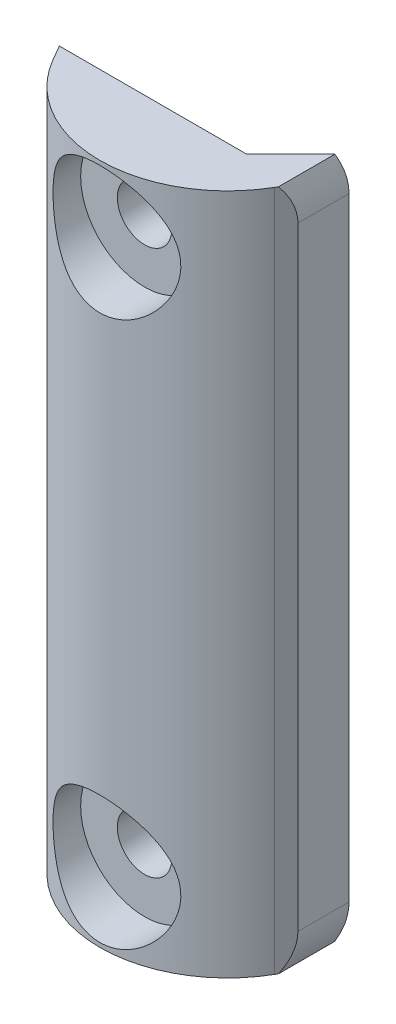
SolidWorks part; units mm, degrees
ref_plane "前视基准面" through (0, 0, 0) normal (0, 0, 1) x (1, 0, 0)
ref_plane "上视基准面" through (0, 0, 0) normal (0, 1, 0) x (1, 0, 0)
ref_plane "右视基准面" through (0, 0, 0) normal (1, 0, 0) x (0, 0, -1)
other "Configuration Table"
sketch "草图1" plane through (0, 0, 0) normal (0, 1, 0) x (1, 0, 0)
  line L0 (-6.4952, -3.75) -> (-7, -2.8756)
  line L1 (-7, -2.8756) -> (7, -2.8756)
  line L2 (7, -2.8756) -> (6.4952, -3.75)
  line L3 (0, -2.8756) -> (0, 0) construction
  arc A0 (-6.4952, -3.75) -> (6.4952, -3.75) centre (0, 0) ccw
  dimension "D1" = 30
  dimension "D3" = 15
  dimension "D2" = 14
extrude "凸台-拉伸1" add sketch "草图1" along normal blind 40
sketch "草图3" plane through (0, 0, 2.8756) normal (0, 0, -1) x (-1, 0, 0)
  line L0 (-7, 0) -> (7, 0) construction
  line L1 (0, 4) -> (0, 0) construction
  line L2 (-7, 40) -> (7, 40) construction
  line L3 (0, 36) -> (0, 4) construction
  circle A0 centre (0, 4) radius 1.6
  circle A1 centre (0, 36) radius 1.6
  dimension "D1" = 3.2
  dimension "D3" = 4
  dimension "D2" = 4
extrude "切除-拉伸1" cut sketch "草图3" against normal up to next
sketch "草图4" plane through (0, 0, 2.8756) normal (0, 0, -1) x (-1, 0, 0)
  circle A0 centre (0, 4) radius 3.75
  circle A1 centre (0, 36) radius 3.75
  dimension "D1" = 7.5
extrude "切除-拉伸2" cut sketch "草图4" against normal up to next from offset 2 offset against normal yes
sketch "草图6" plane through (0, 0, 2.8756) normal (0, 0, -1) x (-1, 0, 0)
  line L7 (7, 20) -> (-7, 20) construction
  line L8 (7, 40) -> (7, 0) construction
  line L9 (-7, 40) -> (-7, 0) construction
  line L10 (-7, -3) -> (7, -3) construction
  line L11 (-7, 2) -> (-7, 0)
  line L12 (-7, 0) -> (-6.5826, 0)
  line L13 (-7, 0) -> (7, 0) construction
  line L14 (-7, 40) -> (-6.5826, 40)
  line L15 (-7, 38) -> (-7, 40)
  arc A2 (-7, 2) -> (-6.5826, 0) centre (-2, 2) ccw
  circle A3 centre (0, 4) radius 1.6 construction
  arc A4 (-7, 38) -> (-6.5826, 40) centre (-2, 38) cw
  point P7 (-6.5772, 0)
  dimension "D1" = 7
  dimension "D2" = 10
extrude "切除-拉伸3" cut sketch "草图6" against normal up to next
sketch "草图7" plane through (0, 0, 0) normal (0, 1, 0) x (1, 0, 0)
  line L0 (7, -2.8756) -> (7, 0.1244)
  line L1 (7, -2.8756) -> (6.5826, -2.8756) construction
  line L2 (6.5826, -3.5986) -> (7, -2.8756) construction
  line L3 (7, 0.1244) -> (4, -2.8756)
  line L4 (6.5826, -2.8756) -> (-7, -2.8756) construction
  line L5 (4, -2.8756) -> (7, -2.8756)
  dimension "D1" = 3
  dimension "D2" = 3
extrude "凸台-拉伸2" add sketch "草图7" along normal up to surface (40 mm away) up to face at (1.233, 40, 4.12)
sketch "草图8" plane through (0, 0, 2.8756) normal (0, 0, 1) x (1, 0, 0)
  line L2 (7, 38) -> (7, 40)
  line L3 (7, 40) -> (6.5826, 40)
  line L4 (7, 38) -> (7, 40)
  line L5 (7, 40) -> (6.5826, 40)
  line L6 (6.5826, 0) -> (7, 0)
  line L7 (7, 0) -> (7, 2)
  line L8 (6.5826, 0) -> (7, 0)
  line L9 (7, 0) -> (7, 2)
  arc A1 (7, 38) -> (6.5826, 40) centre (2, 38) ccw
  arc A2 (7, 38) -> (6.5826, 40) centre (2, 38) ccw
  arc A3 (6.5826, 0) -> (7, 2) centre (2, 2) ccw
  arc A4 (6.5826, 0) -> (7, 2) centre (2, 2) ccw
  dimension "D1" = 0
  dimension "D2" = 0
extrude "切除-拉伸4" cut sketch "草图8" against normal up to next
